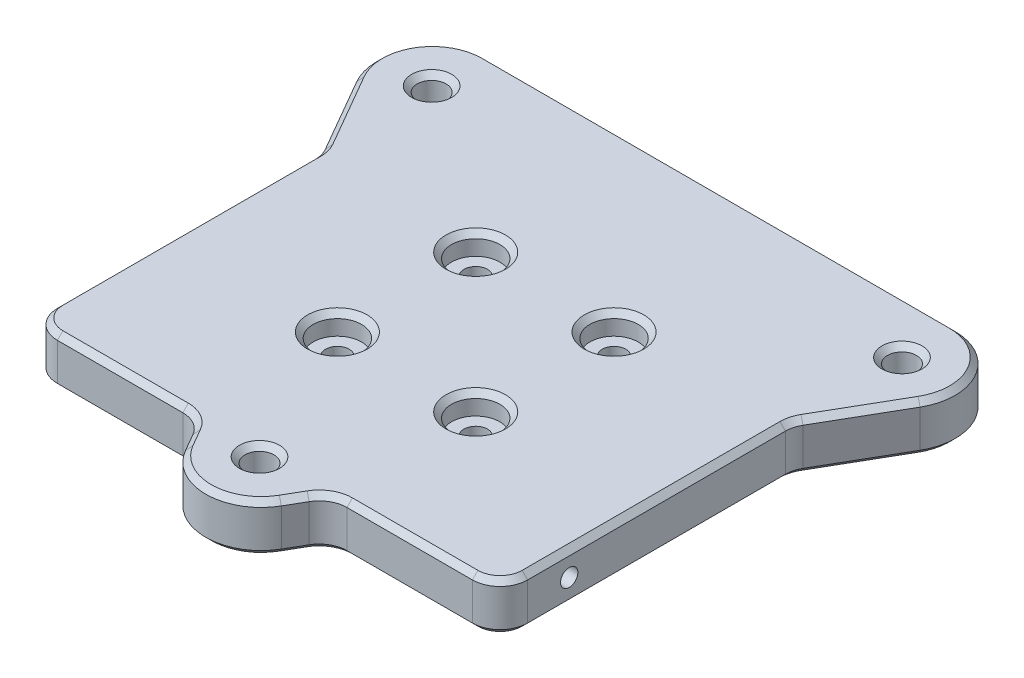
SolidWorks part; units mm, degrees
ref_plane "Front Plane" through (0, 0, 0) normal (0, 0, 1) x (1, 0, 0)
ref_plane "Top Plane" through (0, 0, 0) normal (0, 1, 0) x (1, 0, 0)
ref_plane "Right Plane" through (0, 0, 0) normal (1, 0, 0) x (0, 0, -1)
sketch "Sketch1" plane through (0, 0, 0) normal (0, 1, 0) x (1, 0, 0)
  line L0 (0, -45.0333) -> (0, 0) construction
  line L1 (0, 0) -> (-39, 22.5167) construction
  line L2 (-39, 22.5167) -> (39, 22.5167) construction
  line L3 (39, 22.5167) -> (0, 0) construction
  line L4 (-39, 22.5167) -> (0, -45.0333) construction
  line L5 (0, -45.0333) -> (39, 22.5167) construction
  line L6 (0, -55.0333) -> (47.6603, 27.5167)
  line L7 (-47.6603, 27.5167) -> (47.6603, 27.5167)
  line L8 (-47.6603, 27.5167) -> (0, -55.0333)
  dimension "D2" = 78
  dimension "D1" = 5
extrude "Boss-Extrude1" add sketch "Sketch1" along normal blind 7
sketch "Sketch3" plane through (0, 0, 0) normal (0, 1, 0) x (1, 0, 0)
  line L0 (0, 0) -> (0, -8) construction
  line L1 (-34, -38.4833) -> (34, -38.4833)
  line L2 (-34, -38.4833) -> (-34, 27.5167)
  line L3 (-34, 27.5167) -> (34, 27.5167)
  line L4 (34, -38.4833) -> (34, 27.5167)
  line L5 (47.6603, 27.5167) -> (-47.6603, 27.5167) construction
  line L6 (0, 0) -> (0, 27.5167) construction
  dimension "D1" = 68
  dimension "D2" = 66
  dimension "D3" = 8
extrude "Boss-Extrude2" add sketch "Sketch3" along normal up to surface (7 mm away) up to face at (0, 7, 0)
sketch "Sketch5" plane through (0, 7, 0) normal (0, 1, 0) x (1, 0, 0)
  line L0 (0, 0) -> (0, -39.2598) construction
  line L1 (-34, 19.6299) -> (0, 0) construction
  line L2 (0, 0) -> (34, 19.6299) construction
  line L3 (-34, 19.6299) -> (34, 19.6299) construction
  line L4 (-34, 19.6299) -> (0, -39.2598) construction
  line L5 (0, -39.2598) -> (34, 19.6299) construction
  circle A0 centre (-34, 19.6299) radius 1
  circle A1 centre (34, 19.6299) radius 1
  circle A2 centre (0, -39.2598) radius 1
  dimension "D1" = 2
  dimension "D2" = 68
extrude "Hole Positions" cut sketch "Sketch5" against normal through all
hole_wizard "M5x0.8 Tapped Hole1" positions "Sketch6" profile "Sketch7" tap size "M5x0.8" standard "ANSI Metric" end condition through all
sketch "Sketch6" plane through (0, 7, 0) normal (0, 1, 0) x (1, 0, 0)
  point P0 (-34, 19.6299)
  point P3 (34, 19.6299)
  point P6 (0, -39.2598)
sketch "Sketch7" plane through (-34, 7, -19.6299) normal (1, 0, 0) x (0, 0, 1)
  line L0 (0, 0) -> (0, 7)
  line L1 (0, 7) -> (2.1, 7)
  line L2 (2.1, 7) -> (2.1, 0)
  line L5 (2.1, 0) -> (0, 0)
  line L11 (0, -6.35) -> (0, 107.95) construction
  dimension "Thru Tap Drill Dia." = 4.2
  dimension "Thru Tap Drill Depth" = 7
cosmetic thread "Hole Thread1" parameters "D2"=5
cosmetic thread "Hole Thread2" parameters "D2"=5
cosmetic thread "Hole Thread3" parameters "D2"=5
hole_wizard "CBORE for M3 SHCS1" positions "Sketch8" profile "Sketch9" counterbore size "M3" standard "ANSI Metric" end condition through all
sketch "Sketch8" plane through (0, 7, 0) normal (0, 1, 0) x (1, 0, 0)
  line L1 (-10, -18) -> (10, -18) construction
  line L2 (-10, -18) -> (-10, 2) construction
  line L3 (-10, 2) -> (10, 2) construction
  line L4 (10, -18) -> (10, 2) construction
  line L5 (-10, -18) -> (10, 2) construction
  line L6 (-10, 2) -> (10, -18) construction
  line L7 (0, -8) -> (0, 0) construction
  point P0 (-10, 2)
  point P2 (10, 2)
  point P4 (10, -18)
  point P6 (-10, -18)
  dimension "D1" = 8
  dimension "D2" = 20
sketch "Sketch9" plane through (-10, 7, -2) normal (1, 0, 0) x (0, 0, 1)
  line L0 (0, 0) -> (0, 7)
  line L1 (0, 7) -> (1.7, 7)
  line L3 (1.7, 7) -> (1.7, 3)
  line L4 (1.7, 3) -> (3.5, 3)
  line L5 (3.5, 3) -> (3.5, 0)
  line L7 (3.5, 0) -> (0, 0)
  line L11 (0, -6.35) -> (0, 107.95) construction
  dimension "Thru Hole Dia." = 3.4
  dimension "Thru Hole Depth" = 7
  dimension "C'Bore Dia." = 7
  dimension "C'Bore Depth" = 3
fillet "Fillet1" radius 8 3 edges at (47.6603, 3.5, -27.5167) (-47.6603, 3.5, -27.5167) (0, 3.5, 55.0333)
fillet "Fillet2" radius 4 6 edges at (-34, 3.5, -3.8564) (-34, 3.5, 38.4833) (-9.5551, 3.5, 38.4833) (9.5551, 3.5, 38.4833) (34, 3.5, -3.8564) (34, 3.5, 38.4833)
hole_wizard "M3x0.5 Tapped Hole1" positions "3DSketch1" profile "Sketch10" tap size "M3x0.5" standard "ANSI Metric"
sketch3d "3DSketch1"
  line L0 (0, 3.5, -27.5167) -> (0, 7, -27.5167) construction
  line L1 (33.8038, 7, -27.5167) -> (-33.8038, 7, -27.5167) construction
  line L2 (-34, 7, -2.7846) -> (-34, 7, 34.4833) construction
  line L3 (-34, 0, 34.4833) -> (-34, 7, 34.4833) construction
  line L4 (34, 7, 34.4833) -> (34, 0, 34.4833) construction
  line L5 (34, 3.5, 28.4833) -> (34, 7, 28.4833) construction
  line L6 (34, 7, 34.4833) -> (34, 7, -2.7846) construction
  point P0 (-34, 3.5, 28.4833)
  point P2 (34, 3.5, 28.4833)
  point P4 (0, 3.5, -27.5167)
  dimension "D4" = 6
  dimension "D1" = 3.5
  dimension "D2" = 3.5
  dimension "D3" = 6
  dimension "D5" = 3.5
sketch "Sketch10" plane through (-34, 3.5, 28.4833) normal (0, 1, 0) x (0, 0, 1)
  line L0 (0, 0) -> (0, 8.2511)
  line L1 (0, 8.2511) -> (1.25, 7.5)
  line L2 (1.25, 7.5) -> (1.25, 0)
  line L5 (1.25, 0) -> (0, 0)
  line L10 (0, 8.2511) -> (-1.25, 7.5) construction
  line L11 (0, -6.35) -> (0, 107.95) construction
  dimension "Tap Drill Dia." = 2.5
  dimension "Tap Drill Depth" = 7.5
  dimension "Drill Angle" = 118
cosmetic thread "Hole Thread4" parameters "D1"=6, "D2"=3
cosmetic thread "Hole Thread5" parameters "D1"=6, "D2"=3
cosmetic thread "Hole Thread6" parameters "D1"=6, "D2"=3
chamfer "Chamfer1" distance 0.8 angle 45 50 edges at (-34, 7, 15.8494) (-34, 0, 15.8494) (0, 0, -27.5167) (-40.7321, 0, -23.5167) (-37.634, 0, -10.1506) (-34.1363, 0, -3.8199) (-32.8284, 0, 37.3118) (-20.9323, 7, 38.4833) (-20.9323, 0, 38.4833) (-9.8645, 0, 39.0192) (-7.6643, 0, 41.7583) (0, 0, 47.0333) (7.6643, 0, 41.7583) (9.8645, 0, 39.0192) (20.9323, 7, 38.4833) (20.9323, 0, 38.4833) (32.8284, 0, 37.3118) (34, 0, 15.8494) (34, 7, 15.8494) (34.1363, 0, -3.8199) (37.634, 0, -10.1506) (40.7321, 0, -23.5167) (0, 7, -27.5167) (37.634, 7, -10.1506) (34.1363, 7, -3.8199) (32.8284, 7, 37.3118) (9.8645, 7, 39.0192) (-9.8645, 7, 39.0192) (-32.8284, 7, 37.3118) (-34.1363, 7, -3.8199) (-37.634, 7, -10.1506) (40.7321, 7, -23.5167) (7.6643, 7, 41.7583) (0, 7, 47.0333) (-7.6643, 7, 41.7583) (-40.7321, 7, -23.5167) (0, 7, 41.3598) (34, 7, -17.5299) (-34, 7, -17.5299) (0, 0, 41.3598) (34, 0, -17.5299) (-34, 0, -17.5299) (-10, 7, 21.5) (10, 7, 21.5) (10, 7, 1.5) (-10, 7, 1.5) (-10, 0, 19.7) (10, 0, 19.7) (10, 0, -0.3) (-10, 0, -0.3)
equation "\"TriangleOffset\"=8"
equation "\"D3@Sketch3\"= \"TriangleOffset\""
equation "\"D1@Sketch8\"=\"TriangleOffset\""
equation "\"D4@3DSketch1\"=\"D3@3DSketch1\""
equation "\"D5@3DSketch1\"=\"D1@3DSketch1\""
equation "\"D2@3DSketch1\"=\"D1@3DSketch1\""
